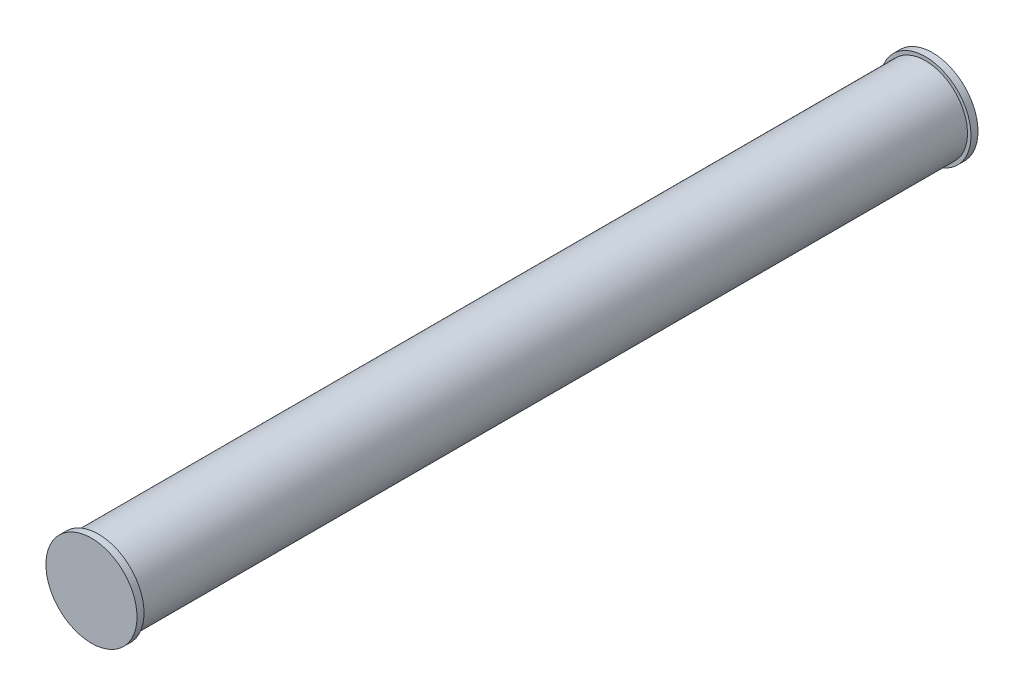
SolidWorks part; units mm, degrees
material "AISI 1020 Steel, Cold Rolled"
ref_plane "Front Plane" through (0, 0, 0) normal (0, 0, 1) x (1, 0, 0)
ref_plane "Top Plane" through (0, 0, 0) normal (0, 1, 0) x (1, 0, 0)
ref_plane "Right Plane" through (0, 0, 0) normal (1, 0, 0) x (0, 0, -1)
sketch "Sketch1" plane through (0, 0, 0) normal (0, 0, 1) x (1, 0, 0)
  circle A0 centre (0, 0) radius 15.24
  dimension "D1" = 30.48
extrude "Boss-Extrude1" add sketch "Sketch1" along normal mid plane 304.8
sketch "Sketch2" plane through (0, 0, 152.4) normal (0, 0, 1) x (1, 0, 0)
  circle A0 centre (0, 0) radius 16.51
  dimension "D1" = 33.02
extrude "Boss-Extrude2" add sketch "Sketch2" against normal blind 2.54
mirror "Mirror1" about plane through (0, 0, 0) normal (0, 0, 1) of "Boss-Extrude2"
